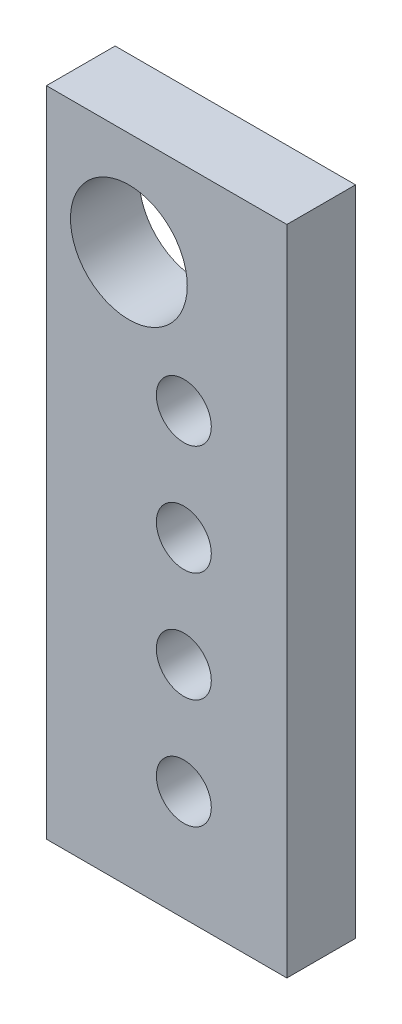
SolidWorks part; units mm, degrees
ref_plane "Alzado" through (0, 0, 0) normal (0, 0, 1) x (1, 0, 0)
ref_plane "Planta" through (0, 0, 0) normal (0, 1, 0) x (1, 0, 0)
ref_plane "Vista lateral" through (0, 0, 0) normal (1, 0, 0) x (0, 0, -1)
sketch "Croquis1" plane through (0, 0, 0) normal (0, 0, 1) x (1, 0, 0)
  line L0 (0.5, 0) -> (0, 0) construction
  line L1 (-12, 7.5) -> (12, 7.5)
  line L2 (-12, 7.5) -> (-12, -40)
  line L3 (-12, -40) -> (12, -40)
  line L4 (12, 7.5) -> (12, -40)
  line L5 (0, 0) -> (12, 0) construction
  line L6 (0, 0) -> (0, 7.5) construction
  circle A6 centre (4.5, -8) radius 2
  circle A7 centre (4.5, -16) radius 2
  circle A8 centre (4.5, -24) radius 2
  circle A9 centre (0.5, 0) radius 4.25
  circle A10 centre (4.5, -32) radius 2
  dimension "D1" = 24
  dimension "D2" = 11.5
  dimension "D5" = 8.5
  dimension "D3" = 7.5
  dimension "D4" = 12
  dimension "D6" = 47.5
  dimension "D7" = 7.5
  dimension "D8" = 7.5
  dimension "D9" = 7.5
  dimension "D10" = 2
extrude "Saliente-Extruir1" add sketch "Croquis1" along normal blind 5
sketch "Croquis2" plane through (0, 0, 0) normal (0, 0, -1) x (-1, 0, 0)
  line L0 (12, 7.5) -> (12, -40) construction
  line L1 (5.5, 7.5) -> (12, 7.5)
  line L3 (5.5, -43.694) -> (12, -43.694)
  line L4 (12, 7.5) -> (12, -43.694)
  line L8 (5.5, -21.715) -> (5.5, -29.215)
  line L9 (5.5, 7.5) -> (5.5, -29.215)
  line L10 (5.5, -29.215) -> (5.5, -43.694)
  line L11 (-12, -40) -> (-12, 7.5) construction
  dimension "D1" = 17.5
extrude "Cortar-Extruir2" cut sketch "Croquis2" against normal blind 5 contours L9 L1 L4 L3 L10
